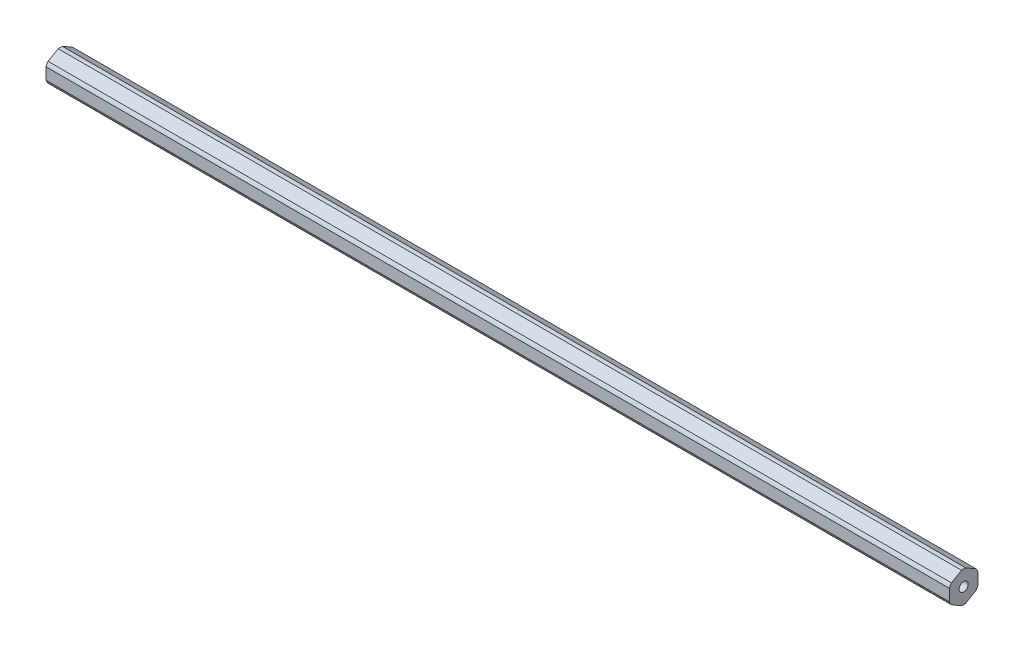
SolidWorks part; units mm, degrees
material "7075-T6 (SN)"
ref_plane "Front Plane" through (0, 0, 0) normal (0, 0, 1) x (1, 0, 0)
ref_plane "Top Plane" through (0, 0, 0) normal (0, 1, 0) x (1, 0, 0)
ref_plane "Right Plane" through (0, 0, 0) normal (1, 0, 0) x (0, 0, -1)
sketch "Sketch1" plane through (0, 0, 0) normal (1, 0, 0) x (0, 0, -1)
  line L1 (0, 7.3323) -> (-6.35, 3.6662)
  line L2 (-6.35, 3.6662) -> (-6.35, -3.6662)
  line L3 (-6.35, -3.6662) -> (0, -7.3323)
  line L4 (0, -7.3323) -> (6.35, -3.6662)
  line L5 (6.35, -3.6662) -> (6.35, 3.6662)
  line L6 (6.35, 3.6662) -> (0, 7.3323)
  circle A1 centre (0, 0) radius 6.858
  circle A2 centre (0, 0) radius 6.35 construction
  dimension "D1" = 13.716
  dimension "D2" = 12.7
extrude "Boss-Extrude1" add sketch "Sketch1" along normal mid plane 400.05 contours L5 A1 L6 L1 L2 L3 L4
sketch "Sketch3" plane through (-200.025, 0, 0) normal (-1, 0, 0) x (0, 0, 1)
  circle A0 centre (0, 0) radius 6.35
  dimension "D1" = 12.7
hole_wizard "#10-32 Tapped Hole1" positions "3DSketch1" profile "Sketch4" tap size "#10-32" standard "ANSI Inch"
sketch3d "3DSketch1"
  line L0 (200.025, 0, 0) -> (-200.025, 0, 0) construction
  point P0 (-200.025, 0, 0)
  point P3 (200.025, 0, 0)
sketch "Sketch4" plane through (-200.025, 0, 0) normal (0, 1, 0) x (0, 0, 1)
  line L0 (0, 0) -> (0, 17.5608)
  line L1 (0, 17.5608) -> (2.0193, 16.3474)
  line L2 (2.0193, 16.3474) -> (2.0193, 0)
  line L5 (2.0193, 0) -> (0, 0)
  line L10 (0, 17.5608) -> (-2.0193, 16.3474) construction
  line L11 (0, -6.35) -> (0, 107.95) construction
  dimension "Tap Drill Dia." = 4.0386
  dimension "Tap Drill Depth" = 16.3474
  dimension "Drill Angle" = 118
cosmetic thread "Hole Thread1" parameters "D1"=13.97, "D2"=4.826
cosmetic thread "Hole Thread2" parameters "D1"=13.97, "D2"=4.826
